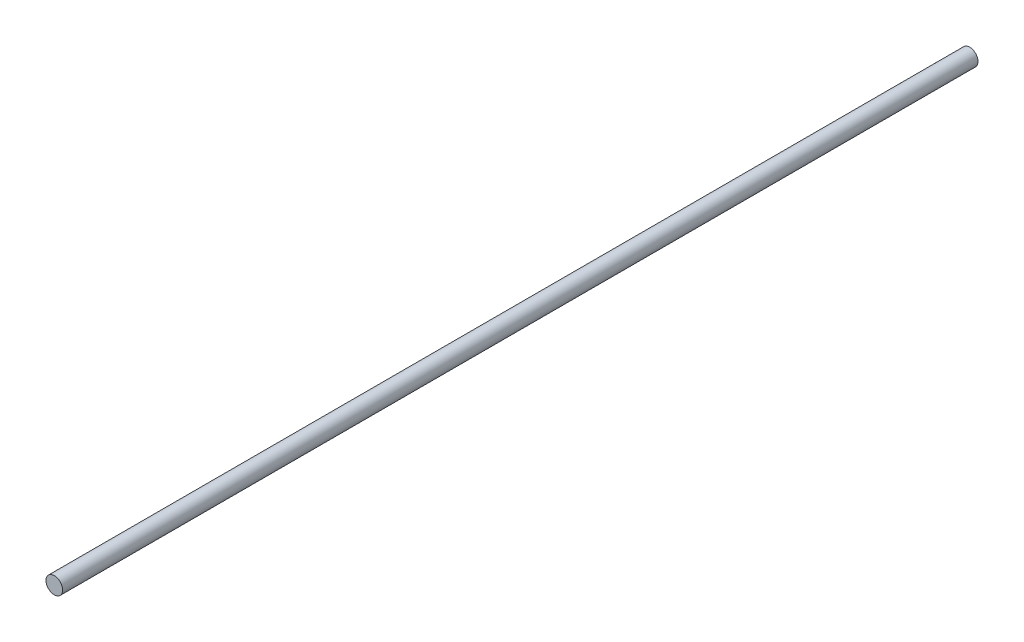
SolidWorks part; units mm, degrees
ref_plane "Front Plane" through (0, 0, 0) normal (0, 0, 1) x (1, 0, 0)
ref_plane "Top Plane" through (0, 0, 0) normal (0, 1, 0) x (1, 0, 0)
ref_plane "Right Plane" through (0, 0, 0) normal (1, 0, 0) x (0, 0, -1)
ref_plane "Plane1" through (0, -54.8048, 0) normal (0, 1, 0) x (1, 0, 0)
sketch "Sketch1" plane through (0, -54.8048, 0) normal (0, 1, 0) x (1, 0, 0)
  line L0 (589.8288, -372.1567) -> (585.8288, -372.1567)
  line L1 (585.8288, -372.1567) -> (585.8288, -812.1567)
  line L2 (585.8288, -812.1567) -> (589.8288, -812.1567)
  line L3 (589.8288, -812.1567) -> (589.8288, -372.1567)
  line L4 (585.8288, -372.1567) -> (585.8288, -812.1567) construction
revolve "Revolve1" add sketch "Sketch1" angle 360 about L4
